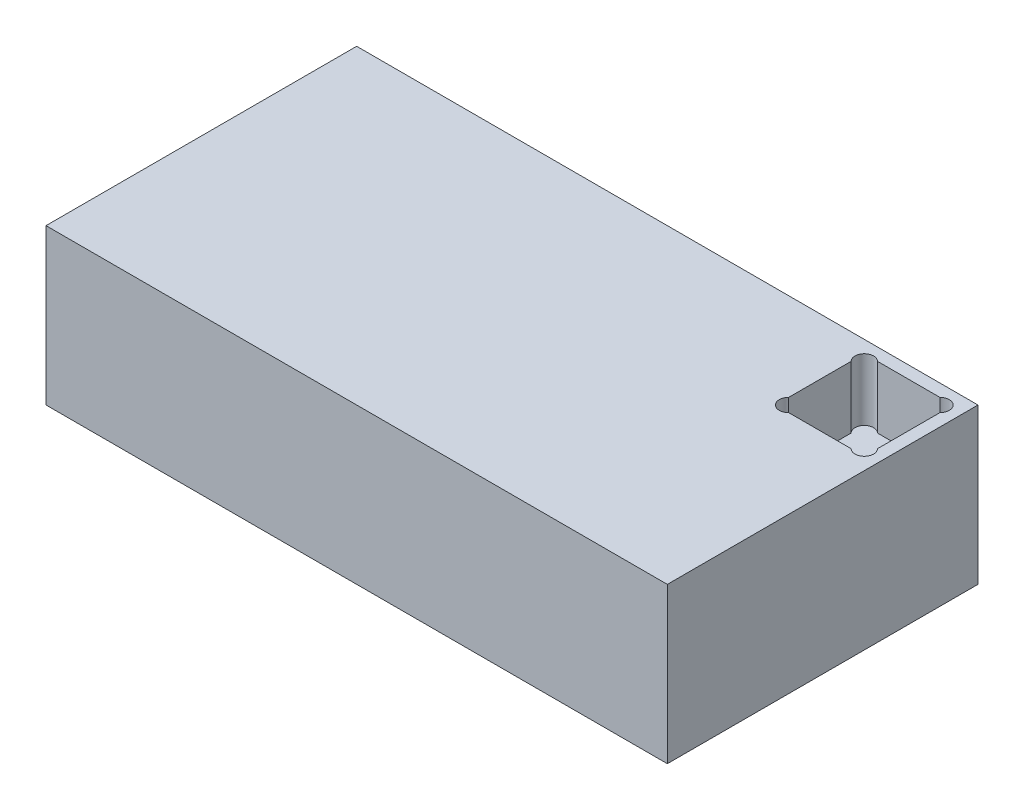
SolidWorks part; units mm, degrees
ref_plane "Front Plane" through (0, 0, 0) normal (0, 0, 1) x (1, 0, 0)
ref_plane "Top Plane" through (0, 0, 0) normal (0, 1, 0) x (1, 0, 0)
ref_plane "Right Plane" through (0, 0, 0) normal (1, 0, 0) x (0, 0, -1)
sketch "Sketch1" plane through (0, 0, 0) normal (0, 1, 0) x (1, 0, 0)
  line L1 (-50, 25) -> (50, 25)
  line L2 (-50, 25) -> (-50, -25)
  line L3 (-50, -25) -> (50, -25)
  line L4 (50, 25) -> (50, -25)
  line L5 (-50, 25) -> (50, -25) construction
  line L6 (-50, -25) -> (50, 25) construction
  point P0 (0, 0)
  dimension "D1" = 100
  dimension "D2" = 50
extrude "Boss-Extrude1" add sketch "Sketch1" against normal blind 25
sketch "Sketch2" plane through (0, 0, 0) normal (0, 1, 0) x (1, 0, 0)
  line L4 (50, -25) -> (50, 25) construction
  line L5 (33.7, 20.8787) -> (33.7, 10.8213)
  line L6 (33.7, 23) -> (48, 23) construction
  line L7 (33.7, 23) -> (33.7, 8.7) construction
  line L8 (33.7, 8.7) -> (48, 8.7) construction
  line L9 (48, 23) -> (48, 8.7) construction
  line L10 (33.7, 23) -> (48, 8.7) construction
  line L11 (33.7, 8.7) -> (48, 23) construction
  line L12 (35.8213, 8.7) -> (45.8787, 8.7)
  line L13 (48, 20.8787) -> (48, 10.8213)
  line L14 (35.8213, 23) -> (45.8787, 23)
  line L15 (50, 25) -> (-50, 25) construction
  arc A4 (33.7, 20.8787) -> (35.8213, 23) centre (34.7607, 21.9393) cw
  arc A5 (48, 20.8787) -> (45.8787, 23) centre (46.9393, 21.9393) ccw
  arc A6 (48, 10.8213) -> (45.8787, 8.7) centre (46.9393, 9.7607) cw
  arc A7 (35.8213, 8.7) -> (33.7, 10.8213) centre (34.7607, 9.7607) cw
  point P0 (46.003, 8.8794)
  point P13 (40.85, 15.85)
  dimension "D3" = 2
  dimension "D1" = 1.5
  dimension "D2" = 14.3
  dimension "D4" = 2
extrude "Cut-Extrude1" cut sketch "Sketch2" against normal blind 10
